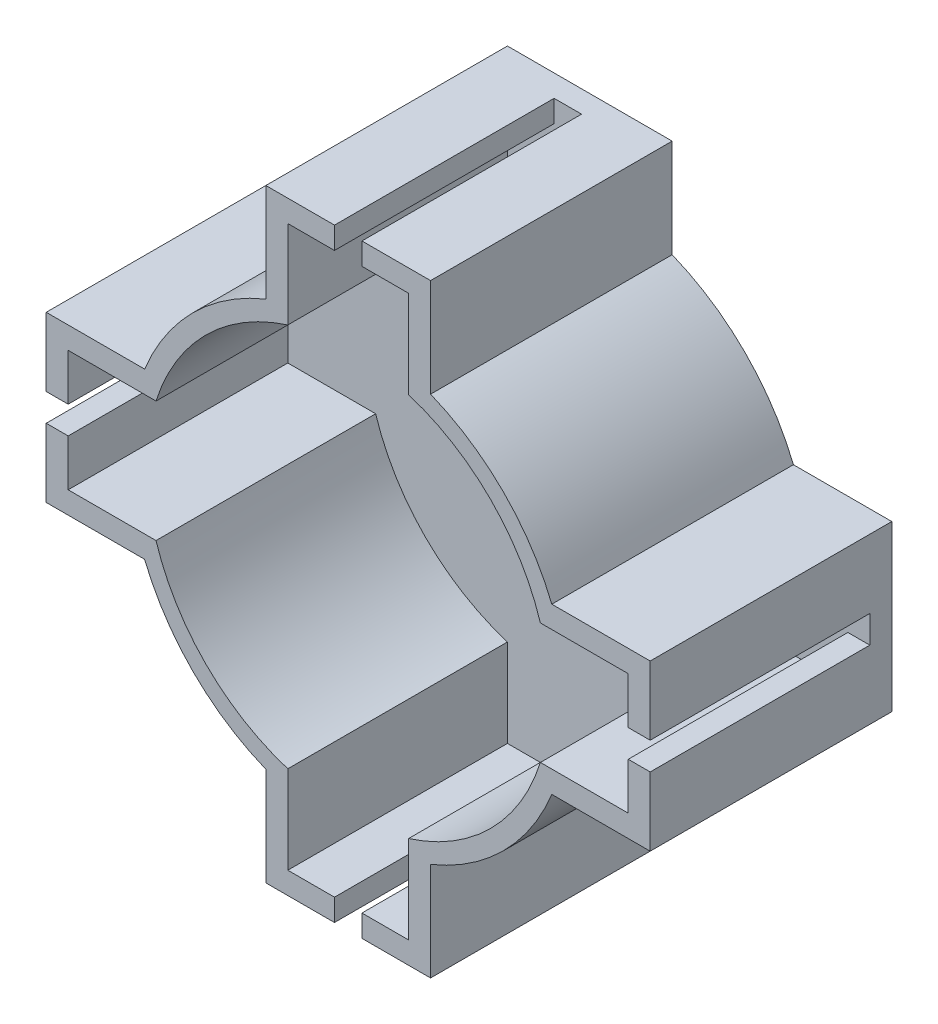
SolidWorks part; units mm, degrees
ref_plane "Alzado" through (0, 0, 0) normal (0, 0, 1) x (1, 0, 0)
ref_plane "Planta" through (0, 0, 0) normal (0, 1, 0) x (1, 0, 0)
ref_plane "Vista lateral" through (0, 0, 0) normal (1, 0, 0) x (0, 0, -1)
sketch "Croquis1" plane through (0, 0, 0) normal (0, 0, 1) x (1, 0, 0)
  line L0 (-68.2215, 9.8461) -> (-68.2215, 13.4299)
  line L1 (-68.2215, 13.4299) -> (-62.2215, 13.4299)
  line L2 (-62.2215, 13.4299) -> (-62.2215, 9.8461)
  line L3 (-57.8053, 5.4299) -> (-54.2215, 5.4299)
  line L4 (-54.2215, 5.4299) -> (-54.2215, -0.5701)
  line L5 (-54.2215, -0.5701) -> (-57.8053, -0.5701)
  line L6 (-62.2215, -4.9863) -> (-62.2215, -8.5701)
  line L7 (-62.2215, -8.5701) -> (-68.2215, -8.5701)
  line L8 (-68.2215, -8.5701) -> (-68.2215, -4.9863)
  line L9 (-72.6377, -0.5701) -> (-76.2215, -0.5701)
  line L10 (-76.2215, -0.5701) -> (-76.2215, 5.4299)
  line L11 (-76.2215, 5.4299) -> (-72.6377, 5.4299)
  arc A1 (-68.2215, -4.9863) -> (-72.6377, -0.5701) centre (-65.2215, 2.4299) cw
  arc A2 (-72.6377, 5.4299) -> (-68.2215, 9.8461) centre (-65.2215, 2.4299) cw
  arc A3 (-62.2215, 9.8461) -> (-57.8053, 5.4299) centre (-65.2215, 2.4299) cw
  arc A4 (-57.8053, -0.5701) -> (-62.2215, -4.9863) centre (-65.2215, 2.4299) cw
extrude "Saliente-Extruir1" add sketch "Croquis1" along normal blind 0.8
sketch "Croquis2" plane through (0, 0, 0.8) normal (0, 0, 1) x (1, 0, 0)
  line L0 (-72.6377, -0.5701) -> (-76.2215, -0.5701)
  line L1 (-76.2215, -0.5701) -> (-76.2215, 1.9299)
  line L2 (-76.2215, 5.4299) -> (-72.6377, 5.4299)
  line L3 (-76.2215, 2.9299) -> (-76.2215, 5.4299)
  line L4 (-72.2215, 0.2299) -> (-75.4215, 0.2299)
  line L5 (-76.2215, 1.9299) -> (-75.4215, 1.9299)
  line L6 (-72.2215, 4.6299) -> (-75.4215, 4.6299)
  line L7 (-75.4215, 4.6299) -> (-75.4215, 2.9299)
  line L8 (-68.2215, 9.8461) -> (-68.2215, 13.4299)
  line L9 (-75.4215, 1.9299) -> (-75.4215, 0.2299)
  line L10 (-75.4215, 2.9299) -> (-76.2215, 2.9299)
  line L11 (-68.2215, 13.4299) -> (-65.7215, 13.4299)
  line L12 (-62.2215, 13.4299) -> (-62.2215, 9.8461)
  line L13 (-64.7215, 13.4299) -> (-62.2215, 13.4299)
  line L14 (-67.4215, 9.4299) -> (-67.4215, 12.6299)
  line L15 (-65.7215, 13.4299) -> (-65.7215, 12.6299)
  line L16 (-63.0215, 9.4299) -> (-63.0215, 12.6299)
  line L17 (-63.0215, 12.6299) -> (-64.7215, 12.6299)
  line L18 (-65.7215, 12.6299) -> (-67.4215, 12.6299)
  line L19 (-64.7215, 12.6299) -> (-64.7215, 13.4299)
  line L20 (-57.8053, 5.4299) -> (-54.2215, 5.4299)
  line L21 (-54.2215, 5.4299) -> (-54.2215, 2.9299)
  line L22 (-54.2215, -0.5701) -> (-57.8053, -0.5701)
  line L23 (-54.2215, 1.9299) -> (-54.2215, -0.5701)
  line L24 (-58.2215, 4.6299) -> (-55.0215, 4.6299)
  line L25 (-54.2215, 2.9299) -> (-55.0215, 2.9299)
  line L26 (-58.2215, 0.2299) -> (-55.0215, 0.2299)
  line L27 (-55.0215, 0.2299) -> (-55.0215, 1.9299)
  line L28 (-55.0215, 2.9299) -> (-55.0215, 4.6299)
  line L29 (-55.0215, 1.9299) -> (-54.2215, 1.9299)
  line L30 (-62.2215, -4.9863) -> (-62.2215, -8.5701)
  line L31 (-62.2215, -8.5701) -> (-64.7215, -8.5701)
  line L32 (-68.2215, -8.5701) -> (-68.2215, -4.9863)
  line L33 (-65.7215, -8.5701) -> (-68.2215, -8.5701)
  line L34 (-63.0215, -4.5701) -> (-63.0215, -7.7701)
  line L35 (-64.7215, -8.5701) -> (-64.7215, -7.7701)
  line L36 (-67.4215, -4.5701) -> (-67.4215, -7.7701)
  line L37 (-67.4215, -7.7701) -> (-65.7215, -7.7701)
  line L38 (-64.7215, -7.7701) -> (-63.0215, -7.7701)
  line L39 (-65.7215, -7.7701) -> (-65.7215, -8.5701)
  arc A0 (-72.6377, 5.4299) -> (-68.2215, 9.8461) centre (-65.2215, 2.4299) cw
  arc A1 (-72.2215, 4.6299) -> (-67.4215, 9.4299) centre (-65.2215, 2.4299) cw
  arc A2 (-62.2215, 9.8461) -> (-57.8053, 5.4299) centre (-65.2215, 2.4299) cw
  arc A3 (-63.0215, 9.4299) -> (-58.2215, 4.6299) centre (-65.2215, 2.4299) cw
  arc A4 (-57.8053, -0.5701) -> (-62.2215, -4.9863) centre (-65.2215, 2.4299) cw
  arc A5 (-58.2215, 0.2299) -> (-63.0215, -4.5701) centre (-65.2215, 2.4299) cw
  arc A6 (-68.2215, -4.9863) -> (-72.6377, -0.5701) centre (-65.2215, 2.4299) cw
  arc A7 (-67.4215, -4.5701) -> (-72.2215, 0.2299) centre (-65.2215, 2.4299) cw
  dimension "D3" = 3.2
  dimension "D4" = 3.2
  dimension "D6" = 0.8
  dimension "D1" = 4
  dimension "D2" = 0.8
  dimension "D5" = 1
  dimension "D7" = 0.8
  dimension "D8" = 0.8
extrude "Saliente-Extruir2" add sketch "Croquis2" along normal blind 8
sketch "Croquis3" plane through (0, 0, 0.8) normal (0, 0, 1) x (1, 0, 0)
  circle A0 centre (-65.2215, 2.4299) radius 2.25
extrude "Cortar-Extruir1" cut sketch "Croquis3" against normal up to vertex (0.8 mm away)
